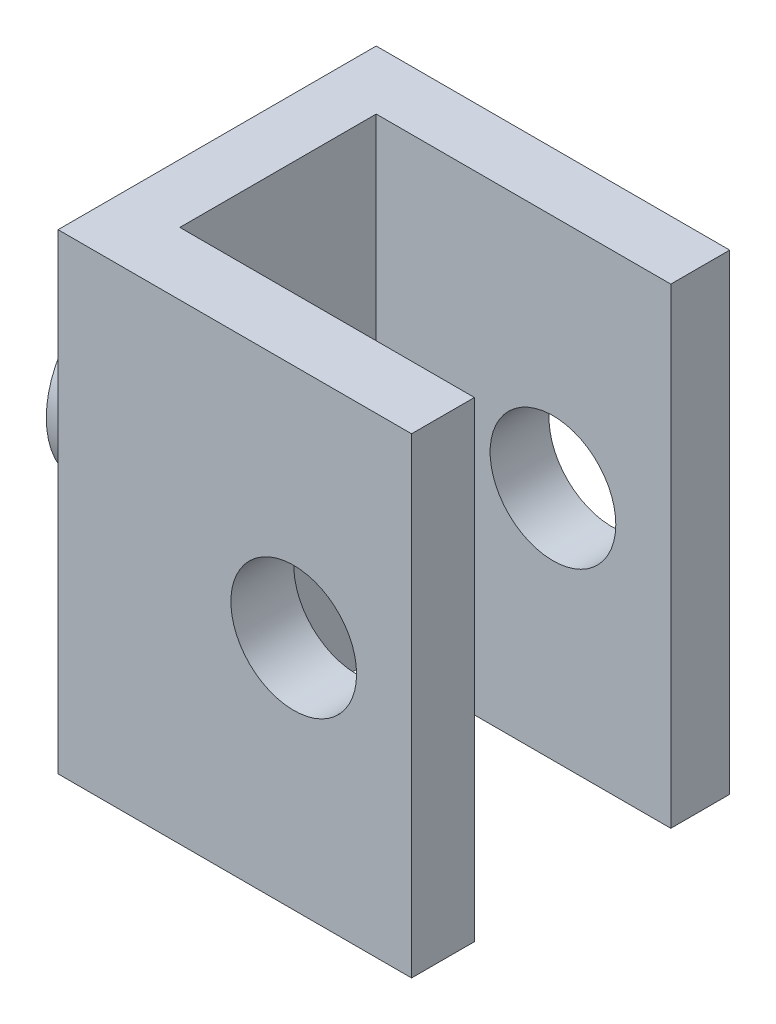
SolidWorks part; units mm, degrees
other "Front Cable Clevis"
ref_plane "Front Plane" through (0, 0, 0) normal (0, 0, 1) x (1, 0, 0)
ref_plane "Top Plane" through (0, 0, 0) normal (0, 1, 0) x (1, 0, 0)
ref_plane "Right Plane" through (0, 0, 0) normal (1, 0, 0) x (0, 0, -1)
sketch3d "Spring Front Cable Clevis 1 sketch datum points"
  point P0 (-42.2917, -18, 11)
  point P1 (-32.2917, -18, 11)
  point P2 (-42.2917, -8, 11)
ref_plane "Spring Front Cable Clevis 1 sketch plane" through (0, 0, 11) normal (0, 0, 1) x (1, 0, 0)
sketch "Spring Front Cable Clevis 1 sketch" plane through (0, 0, 11) normal (0, 0, 1) x (1, 0, 0)
  line L0 (-42.2917, -18) -> (-40.7917, -18)
  line L1 (-40.7917, -18) -> (-40.7917, -6)
  line L2 (-40.7917, -6) -> (-42.2917, -6)
  line L3 (-42.2917, -6) -> (-42.2917, -18)
extrude "Spring Front Cable Clevis 1" add sketch "Spring Front Cable Clevis 1 sketch" along normal blind 8.1 separate body
sketch3d "Spring Front Clevis 1 Lower sketch datum points"
  point P0 (-40.8917, -18, 11)
  point P1 (-30.8917, -18, 11)
  point P2 (-40.8917, -8, 11)
ref_plane "Spring Front Clevis 1 Lower sketch plane" through (0, 0, 11) normal (0, 0, 1) x (1, 0, 0)
sketch "Spring Front Clevis 1 Lower sketch" plane through (0, 0, 11) normal (0, 0, 1) x (1, 0, 0)
  line L0 (-40.8917, -18) -> (-33.2917, -18)
  line L1 (-33.2917, -18) -> (-33.2917, -6)
  line L2 (-33.2917, -6) -> (-40.8917, -6)
  line L3 (-40.8917, -6) -> (-40.8917, -18)
extrude "Spring Front Clevis 1 Lower" add sketch "Spring Front Clevis 1 Lower sketch" along normal blind 1.5
sketch3d "Spring Front Clevis 1 Upper sketch datum points"
  point P0 (-40.8917, -18, 17.5)
  point P1 (-30.8917, -18, 17.5)
  point P2 (-40.8917, -8, 17.5)
ref_plane "Spring Front Clevis 1 Upper sketch plane" through (0, 0, 17.5) normal (0, 0, 1) x (1, 0, 0)
sketch "Spring Front Clevis 1 Upper sketch" plane through (0, 0, 17.5) normal (0, 0, 1) x (1, 0, 0)
  line L0 (-40.8917, -18) -> (-33.2917, -18)
  line L1 (-33.2917, -18) -> (-33.2917, -6)
  line L2 (-33.2917, -6) -> (-40.8917, -6)
  line L3 (-40.8917, -6) -> (-40.8917, -18)
extrude "Spring Front Clevis 1 Upper" add sketch "Spring Front Clevis 1 Upper sketch" along normal blind 1.6
sketch3d "Front Clevis Swage Housing 1 sketch datum points"
  point P0 (-44.2917, -12, 15)
  point P1 (-44.2917, -2, 15)
  point P2 (-44.2917, -12, 25)
ref_plane "Front Clevis Swage Housing 1 sketch plane" through (-44.2917, 0, 0) normal (1, 0, 0) x (0, 0, -1)
sketch "Front Clevis Swage Housing 1 sketch" plane through (-44.2917, 0, 0) normal (1, 0, 0) x (0, 0, -1)
  circle A0 centre (-15, -12) radius 2.4
extrude "Front Clevis Swage Housing 1" add sketch "Front Clevis Swage Housing 1 sketch" along normal blind 2.1
sketch3d "Front Clevis Swage Bore 1 sketch datum points"
  point P0 (-44.3917, -12, 15)
  point P1 (-44.3917, -2, 15)
  point P2 (-44.3917, -12, 25)
ref_plane "Front Clevis Swage Bore 1 sketch plane" through (-44.3917, 0, 0) normal (1, 0, 0) x (0, 0, -1)
sketch "Front Clevis Swage Bore 1 sketch" plane through (-44.3917, 0, 0) normal (1, 0, 0) x (0, 0, -1)
  circle A0 centre (-15, -12) radius 0.75
extrude "Front Clevis Swage Bore 1" cut sketch "Front Clevis Swage Bore 1 sketch" along normal blind 2.15
sketch3d "Front Clevis Pin Bore 1 sketch datum points"
  point P0 (-36.2917, -12, 10.9)
  point P1 (-26.2917, -12, 10.9)
  point P2 (-36.2917, -2, 10.9)
ref_plane "Front Clevis Pin Bore 1 sketch plane" through (0, 0, 10.9) normal (0, 0, 1) x (1, 0, 0)
sketch "Front Clevis Pin Bore 1 sketch" plane through (0, 0, 10.9) normal (0, 0, 1) x (1, 0, 0)
  circle A0 centre (-36.2917, -12) radius 1.6
extrude "Front Clevis Pin Bore 1" cut sketch "Front Clevis Pin Bore 1 sketch" along normal blind 8.3
